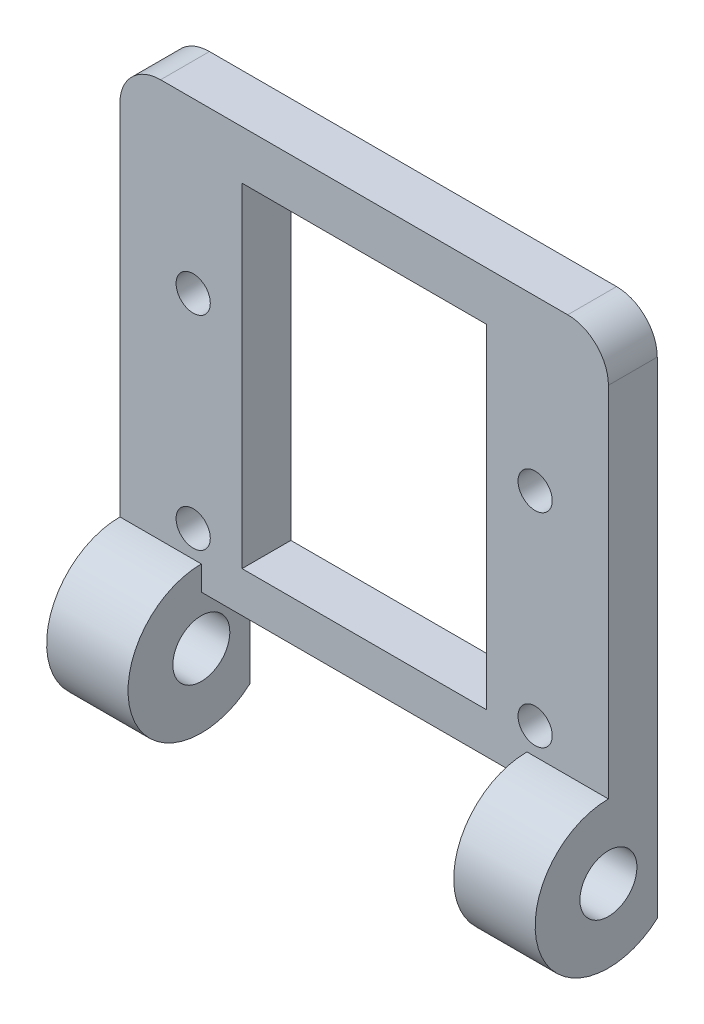
SolidWorks part; units mm, degrees
ref_plane "Plan de face" through (0, 0, 0) normal (0, 0, 1) x (1, 0, 0)
ref_plane "Plan de dessus" through (0, 0, 0) normal (0, 1, 0) x (1, 0, 0)
ref_plane "Plan de droite" through (0, 0, 0) normal (1, 0, 0) x (0, 0, -1)
sketch "Esquisse1" plane through (0, 0, 0) normal (0, 0, 1) x (1, 0, 0)
  line L0 (0, 29.4561) -> (0, -27.4317) construction
  line L1 (15, 13) -> (-15, 13)
  line L2 (15, 13) -> (15, -13)
  line L3 (15, -13) -> (-15, -13)
  line L4 (-15, 13) -> (-15, -13)
  line L5 (15, 13) -> (-15, -13) construction
  line L6 (15, -13) -> (-15, 13) construction
  line L7 (12.5, 12) -> (-12.5, 12) construction
  line L8 (12.5, 12) -> (12.5, -11.862) construction
  line L9 (12.5, -11.862) -> (-12.5, -11.862) construction
  line L10 (-12.5, 12) -> (-12.5, -11.862) construction
  line L11 (12.5, 12) -> (-12.5, -11.862) construction
  line L12 (12.5, -11.862) -> (-12.5, 12) construction
  line L13 (-7.5, 13) -> (-7.5, -10.5) construction
  line L14 (-7.5, -10.5) -> (7.5, -10.5)
  line L15 (7.5, 13) -> (7.5, -10.5) construction
  line L16 (-7.5, 10) -> (7.5, 10)
  line L17 (7.5, 10) -> (7.5, -10.5)
  line L18 (-7.5, 10) -> (-7.5, -10.5)
  circle A0 centre (-10.5, 2.638) radius 1.05
  circle A1 centre (10.5, 2.638) radius 1.05
  circle A2 centre (-10.5, -9.862) radius 1.05
  circle A3 centre (10.5, -9.862) radius 1.05
  point P0 (0, 0)
  point P5 (0, 0.069)
  point P26 (0, -10.5)
  dimension "D4" = 14.5
  dimension "D7" = 2.1
  dimension "D9" = 2
  dimension "D1" = 30
  dimension "D2" = 26
  dimension "D3" = 25
  dimension "D5" = 23.862
  dimension "D6" = 2
  dimension "D8" = 1
  dimension "D10" = 2
  dimension "D11" = 15
  dimension "D12" = 23.5
  dimension "D13" = 3
extrude "Boss.-Extru.1" add sketch "Esquisse1" along normal blind 3 contours L1 L15 L14 L13 L4 L3 L2 A1 A0 A2 A3
fillet "Congé1" radius 2.5 2 edges at (-15, 13, 1.5) (15, 13, 1.5)
sketch "Esquisse3" plane through (15, 0, 0) normal (1, 0, 0) x (0, 0, -1)
  line L0 (0, 7.0594) -> (0, -12.7792) construction
  line L1 (0, -13) -> (-21.2916, -13) construction
  line L2 (-3, -4.9165) -> (-3, -15.7437) construction
  line L3 (-3, 10.5) -> (-3, -13) construction
  line L5 (-3, -13) -> (0, -13) construction
  line L6 (0, -19.3541) -> (0, -13)
  line L11 (0, -13) -> (0, 10.5)
  line L12 (0, 10.5) -> (-3, 10.5)
  line L13 (-3, 10.5) -> (-3, -13)
  line L14 (-3, -13) -> (0, -13)
  line L15 (0, -13) -> (0, 10.5)
  line L16 (0, 10.5) -> (-3, 10.5)
  line L17 (-3, 10.5) -> (-3, -13)
  line L18 (-3, -13) -> (0, -13)
  circle A0 centre (-3, -16) radius 1.75
  arc A1 (-3, -11.5) -> (0, -19.3541) centre (-3, -16) ccw
  line M12 (-3, -13) -> (0, -13)
  dimension "D1" = 3.5
  dimension "D2" = 4.5
  dimension "D3" = 3
  dimension "D4" = 3
  dimension "D5" = 0
extrude "Boss.-Extru.3" add sketch "Esquisse3" against normal blind 5 contours L17 A1 L6 A0 M12
mirror "Symétrie2" about plane through (0, 0, 0) normal (1, 0, 0) of "Boss.-Extru.3"
